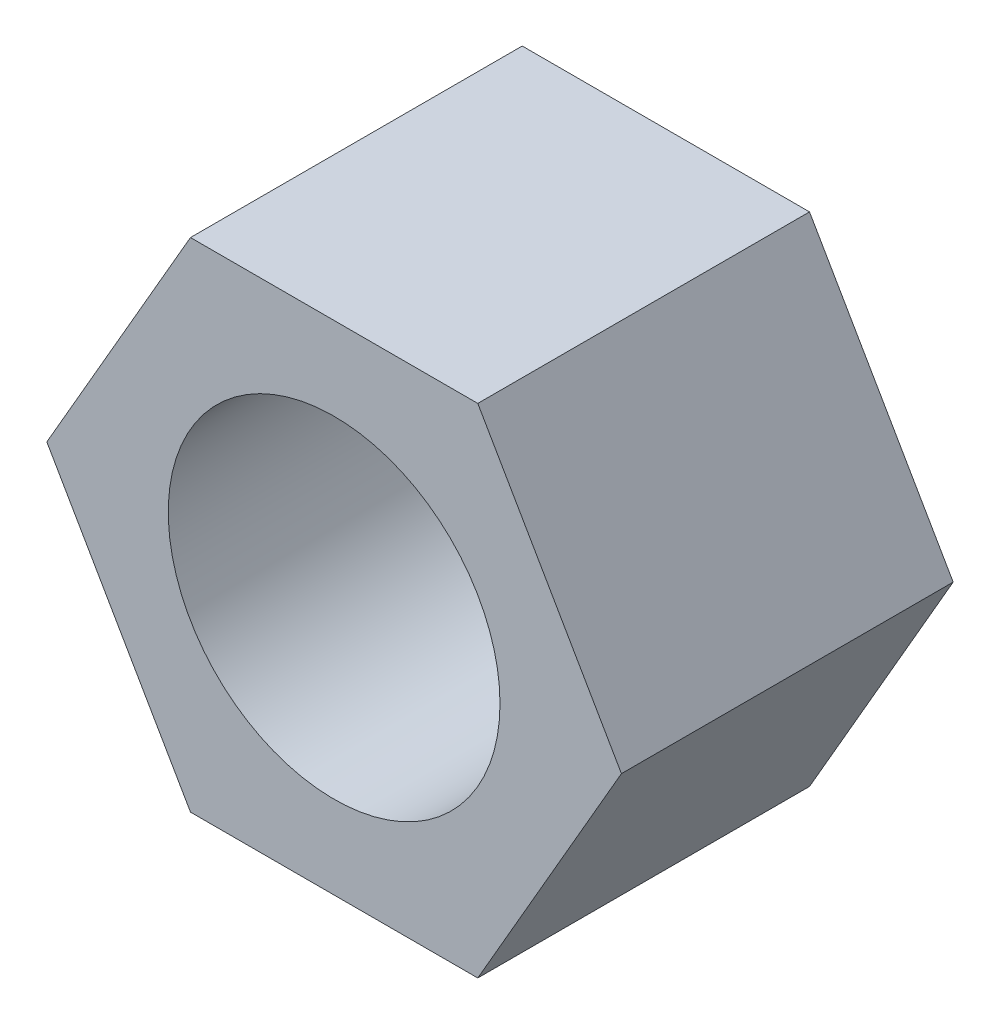
SolidWorks part; units mm, degrees
ref_plane "前视基准面" through (0, 0, 0) normal (0, 0, 1) x (1, 0, 0)
ref_plane "上视基准面" through (0, 0, 0) normal (0, 1, 0) x (1, 0, 0)
ref_plane "右视基准面" through (0, 0, 0) normal (1, 0, 0) x (0, 0, -1)
sketch "草图1" plane through (0, 0, 0) normal (0, 0, 1) x (1, 0, 0)
  line L1 (1.7321, 0) -> (0.866, 1.5)
  line L2 (0.866, 1.5) -> (-0.866, 1.5)
  line L3 (-0.866, 1.5) -> (-1.7321, 0)
  line L4 (-1.7321, 0) -> (-0.866, -1.5)
  line L5 (-0.866, -1.5) -> (0.866, -1.5)
  line L6 (0.866, -1.5) -> (1.7321, 0)
  circle A0 centre (0, 0) radius 1
  circle A1 centre (0, 0) radius 1.5 construction
  dimension "D1" = 2
  dimension "D2" = 3
extrude "凸台-拉伸1" add sketch "草图1" along normal blind 2
